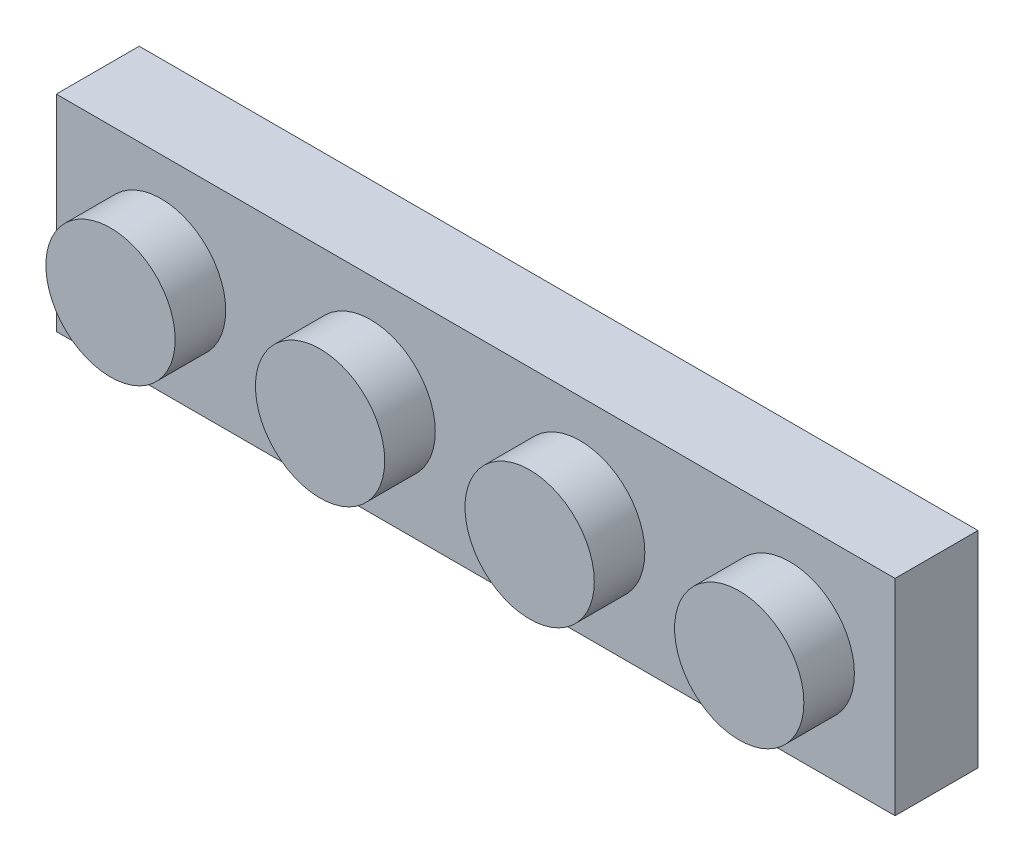
SolidWorks part; units mm, degrees
ref_plane "Front Plane" through (0, 0, 0) normal (0, 0, 1) x (1, 0, 0)
ref_plane "Top Plane" through (0, 0, 0) normal (0, 1, 0) x (1, 0, 0)
ref_plane "Right Plane" through (0, 0, 0) normal (1, 0, 0) x (0, 0, -1)
sketch "Sketch1" plane through (0, 0, 0) normal (0, 0, 1) x (1, 0, 0)
  line L1 (-15.93, 3.905) -> (15.93, 3.905)
  line L2 (-15.93, 3.905) -> (-15.93, -3.905)
  line L3 (-15.93, -3.905) -> (15.93, -3.905)
  line L4 (15.93, 3.905) -> (15.93, -3.905)
  line L5 (-15.93, 3.905) -> (15.93, -3.905) construction
  line L6 (-15.93, -3.905) -> (15.93, 3.905) construction
  point P0 (0, 0)
  dimension "D1" = 7.81
  dimension "D2" = 31.86
extrude "Boss-Extrude1" add sketch "Sketch1" against normal blind 3.15
sketch "Sketch2" plane through (0, 0, 0) normal (0, 0, 1) x (1, 0, 0)
  line L0 (-15.93, 3.905) -> (-15.93, -3.905) construction
  line L1 (-15.93, -3.905) -> (15.93, -3.905) construction
  circle A0 centre (-11.95, 0) radius 2.455
  circle A1 centre (-3.99, 0) radius 2.455
  circle A2 centre (3.97, 0) radius 2.455
  circle A3 centre (11.93, 0) radius 2.455
  dimension "D1" = 4.91
  dimension "D2" = 3.98
  dimension "D5" = 7.96
  dimension "D3" = 3.905
  dimension "D4" = 4
extrude "Boss-Extrude2" add sketch "Sketch2" along normal blind 1.92
shell "Shell1" thickness 1.5
sketch "Sketch3" plane through (0, 0, -1.5) normal (0, 0, -1) x (-1, 0, 0)
  line L1 (-15.93, -3.905) -> (-15.93, 3.905) construction
  line L2 (15.93, -3.905) -> (-15.93, -3.905) construction
  circle A0 centre (-7.965, 0) radius 1.485
  circle A1 centre (-7.965, 0) radius 0.565
  circle A2 centre (0.005, 0) radius 0.565
  circle A3 centre (0.005, 0) radius 1.485
  circle A4 centre (7.975, 0) radius 0.565
  circle A5 centre (7.975, 0) radius 1.485
  dimension "D3" = 2.97
  dimension "D4" = 1.13
  dimension "D6" = 7.97
  dimension "D1" = 7.965
  dimension "D2" = 3.905
  dimension "D5" = 3
extrude "Boss-Extrude3" add sketch "Sketch3" along normal offset from surface (1.45 mm away) 0.2 up to face at (0, 0, -3.15)
